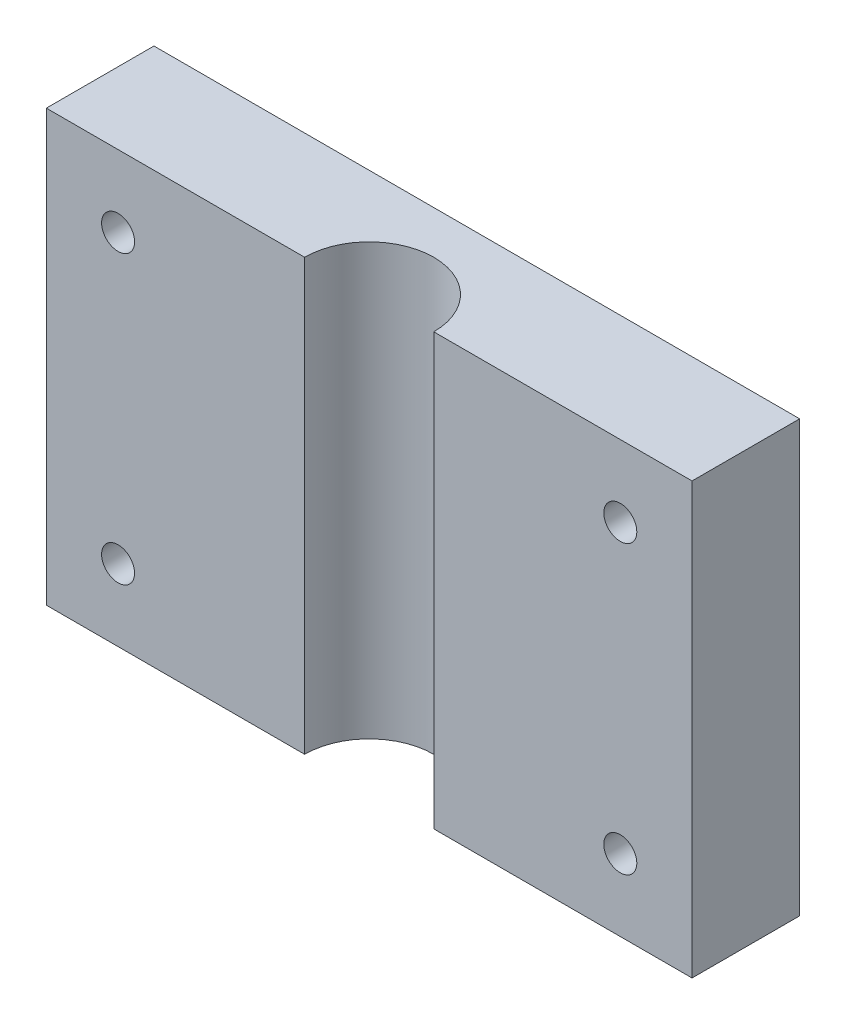
SolidWorks part; units mm, degrees
ref_plane "Front Plane" through (0, 0, 0) normal (0, 0, 1) x (1, 0, 0)
ref_plane "Top Plane" through (0, 0, 0) normal (0, 1, 0) x (1, 0, 0)
ref_plane "Right Plane" through (0, 0, 0) normal (1, 0, 0) x (0, 0, -1)
sketch "Sketch1" plane through (0, 0, 0) normal (0, 0, 1) x (1, 0, 0)
  line L0 (0, -55) -> (0, 55) construction
  line L1 (-45, 30) -> (45, 30)
  line L2 (-45, 30) -> (-45, -30)
  line L3 (-45, -30) -> (45, -30)
  line L4 (45, 30) -> (45, -30)
  line L5 (-45, 30) -> (45, -30) construction
  line L6 (-45, -30) -> (45, 30) construction
  line L7 (55, 0) -> (-55, 0) construction
  circle A0 centre (-35, -20) radius 2.3
  circle A1 centre (35, -20) radius 2.3
  circle A2 centre (35, 20) radius 2.3
  circle A3 centre (-35, 20) radius 2.3
  point P0 (0, 0)
  dimension "D3" = 4.6
  dimension "D1" = 60
  dimension "D2" = 90
  dimension "D4" = 10
  dimension "D5" = 10
extrude "Boss-Extrude1" add sketch "Sketch1" along normal blind 15
sketch "Sketch2" plane through (0, -30, 0) normal (0, -1, 0) x (1, 0, 0)
  line L0 (-45, 15) -> (45, 15) construction
  circle A0 centre (0, 15) radius 9
  dimension "D1" = 18
extrude "Cut-Extrude1" cut sketch "Sketch2" against normal blind 72
